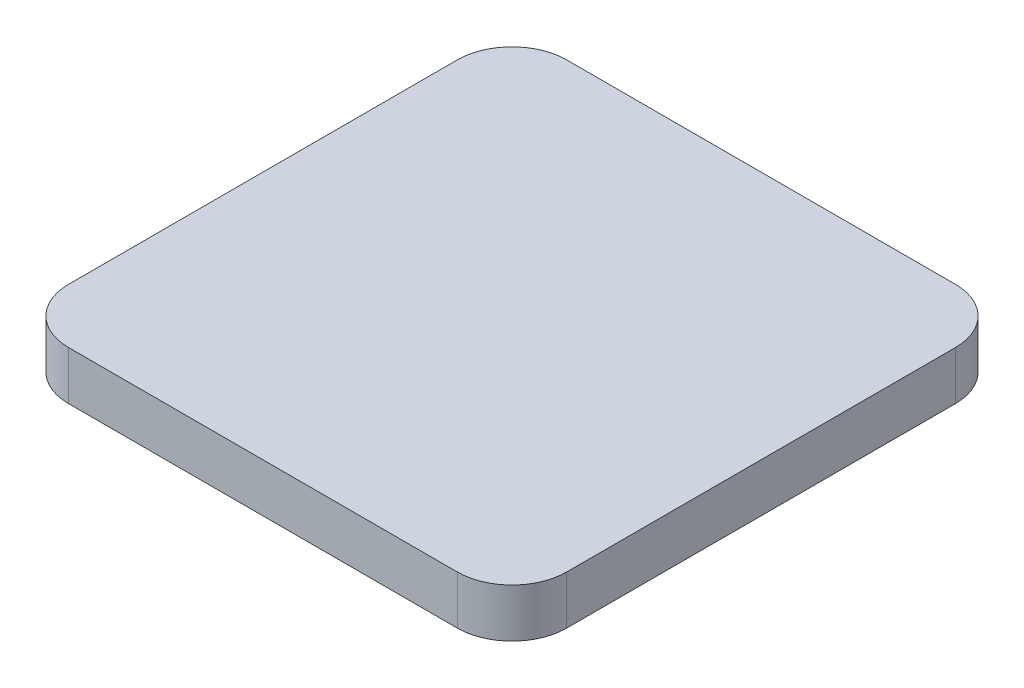
SolidWorks part; units mm, degrees
material "POM Acetal Copolymer"
ref_plane "Front Plane" through (0, 0, 0) normal (0, 0, 1) x (1, 0, 0)
ref_plane "Top Plane" through (0, 0, 0) normal (0, 1, 0) x (1, 0, 0)
ref_plane "Right Plane" through (0, 0, 0) normal (1, 0, 0) x (0, 0, -1)
sketch "Extrude sketch 1" plane through (0, 0, 0) normal (0, 1, 0) x (1, 0, 0)
  line L0 (20.5, 16) -> (20.5, -16)
  line L1 (16, -20.5) -> (-16, -20.5)
  line L2 (-20.5, -16) -> (-20.5, 16)
  line L3 (-16, 20.5) -> (16, 20.5)
  arc A0 (20.5, -16) -> (16, -20.5) centre (16, -16) cw
  arc A1 (-16, -20.5) -> (-20.5, -16) centre (-16, -16) cw
  arc A2 (-20.5, 16) -> (-16, 20.5) centre (-16, 16) cw
  arc A3 (16, 20.5) -> (20.5, 16) centre (16, 16) cw
  dimension "D1" = 4.5
  dimension "D2" = 41
extrude "Extrude 1" add sketch "Extrude sketch 1" along normal blind 4 separate body
